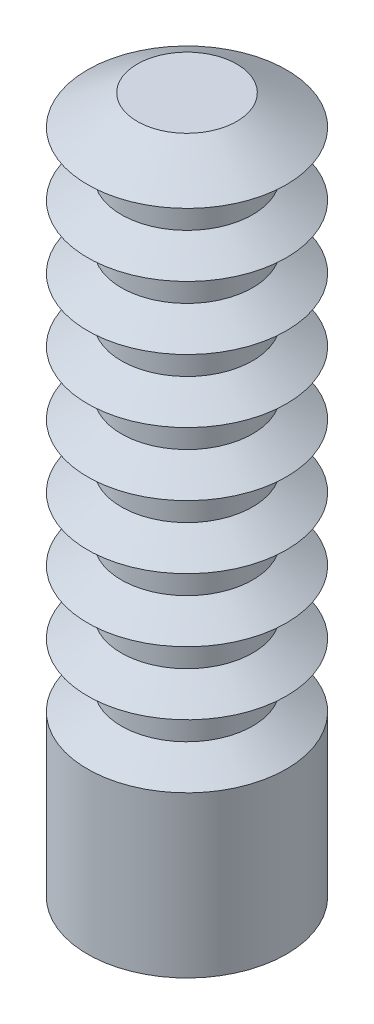
SolidWorks part; units mm, degrees
ref_plane "Front Plane" through (0, 0, 0) normal (0, 0, 1) x (1, 0, 0)
ref_plane "Top Plane" through (0, 0, 0) normal (0, 1, 0) x (1, 0, 0)
ref_plane "Right Plane" through (0, 0, 0) normal (1, 0, 0) x (0, 0, -1)
sketch "Sketch1" plane through (0, 0, 0) normal (0, 0, 1) x (1, 0, 0)
  line L0 (-2.9316, 34.2) -> (-2.9316, 31.2) construction
  line L1 (-0.4316, 32.7) -> (-2.1316, 31.68)
  line L2 (-5.4316, 34.2) -> (-5.4316, 0) construction
  line L3 (-2.1316, 31.68) -> (-2.1316, 30.54)
  line L4 (-2.9316, 34.2) -> (-0.4316, 32.7)
  line L5 (-3.1389, 32.0142) -> (-1.9958, 32.7)
  line L6 (-2.9316, 34.2) -> (-5.4316, 34.2)
  line L7 (-5.4316, 33.4) -> (-3.1389, 33.4)
  line L8 (-0.4316, 0) -> (-0.4316, -0.8)
  line L9 (-2.6564, 33.1045) -> (-3.1389, 33.4)
  line L10 (-3.1389, 33.4) -> (-1.9958, 32.7)
  line L11 (-0.4316, -0.8) -> (-5.4316, -0.8)
  line L12 (-3.1389, 28.8342) -> (-1.9958, 29.52)
  line L13 (-3.1389, 25.6542) -> (-1.9958, 26.34)
  line L14 (-3.1389, 30.22) -> (-3.1389, 32.0142)
  line L15 (-3.1389, 22.4742) -> (-1.9958, 23.16)
  line L16 (-2.1316, 30.54) -> (-0.4316, 29.52)
  line L17 (-3.1389, 19.2942) -> (-1.9958, 19.98)
  line L18 (-3.1389, 30.22) -> (-1.9958, 29.52)
  line L19 (-0.4316, 29.52) -> (-2.1316, 28.5)
  line L20 (-3.1389, 16.1142) -> (-1.9958, 16.8)
  line L21 (-2.1316, 28.5) -> (-2.1316, 27.36)
  line L22 (-3.1389, 27.04) -> (-3.1389, 28.8342)
  line L23 (-2.1316, 27.36) -> (-0.4316, 26.34)
  line L24 (-3.1389, 27.04) -> (-1.9958, 26.34)
  line L25 (-0.4316, 26.34) -> (-2.1316, 25.32)
  line L26 (-3.1389, 12.9342) -> (-1.9958, 13.62)
  line L27 (-2.1316, 25.32) -> (-2.1316, 24.18)
  line L28 (-3.1389, 23.86) -> (-3.1389, 25.6542)
  line L29 (-2.9316, 34.2) -> (-2.9316, 30.7) construction
  line L30 (-5.4316, 34.2) -> (-5.4316, 33.4)
  line L31 (-2.1316, 24.18) -> (-0.4316, 23.16)
  line L32 (-3.1389, 9.7542) -> (-1.9958, 10.44)
  line L33 (-3.1389, 23.86) -> (-1.9958, 23.16)
  line L34 (-5.4316, -0.8) -> (-5.4316, 0)
  line L35 (-0.4316, 23.16) -> (-2.1316, 22.14)
  line L36 (-5.4316, 0) -> (-1.2316, 0)
  line L37 (-2.1316, 22.14) -> (-2.1316, 21)
  line L38 (-3.1389, 20.68) -> (-3.1389, 22.4742)
  line L39 (-2.1316, 21) -> (-0.4316, 19.98)
  line L40 (-3.1389, 20.68) -> (-1.9958, 19.98)
  line L41 (-0.4316, 19.98) -> (-2.1316, 18.96)
  line L43 (-2.1316, 18.96) -> (-2.1316, 17.82)
  line L44 (-3.1389, 17.5) -> (-3.1389, 19.2942)
  line L45 (-2.1316, 17.82) -> (-0.4316, 16.8)
  line L46 (-3.1389, 17.5) -> (-1.9958, 16.8)
  line L47 (-0.4316, 16.8) -> (-2.1316, 15.78)
  line L49 (-2.1316, 15.78) -> (-2.1316, 14.64)
  line L50 (-3.1389, 14.32) -> (-3.1389, 16.1142)
  line L51 (-2.1316, 14.64) -> (-0.4316, 13.62)
  line L52 (-3.1389, 14.32) -> (-1.9958, 13.62)
  line L53 (-0.4316, 13.62) -> (-2.1316, 12.6)
  line L55 (-2.1316, 12.6) -> (-2.1316, 11.46)
  line L56 (-3.1389, 11.14) -> (-3.1389, 12.9342)
  line L57 (-2.1316, 11.46) -> (-0.4316, 10.44)
  line L58 (-3.1389, 11.14) -> (-1.9958, 10.44)
  line L59 (-0.4316, 10.44) -> (-2.1316, 9.42)
  line L60 (-1.9958, 10.44) -> (-3.1543, 9.7449)
  line L61 (-2.1316, 9.42) -> (-2.1316, 8.28)
  line L62 (-3.1389, 7.96) -> (-3.1389, 9.7542)
  line L63 (-2.9316, 31.02) -> (-0.4316, 29.52) [skipped]
  line L64 (-2.1316, 8.28) -> (-0.4316, 7.26)
  line L65 (-2.9316, 27.84) -> (-0.4316, 26.34) [skipped]
  line L66 (-2.9316, 24.66) -> (-0.4316, 23.16) [skipped]
  line L67 (-2.9316, 21.48) -> (-0.4316, 19.98) [skipped]
  line L68 (-2.9316, 18.3) -> (-0.4316, 16.8) [skipped]
  line L69 (-2.9316, 15.12) -> (-0.4316, 13.62) [skipped]
  line L70 (-2.9316, 11.94) -> (-0.4316, 10.44) [skipped]
  line L71 (-3.1389, 7.96) -> (-1.9958, 7.26)
  line L73 (-0.4316, 7.26) -> (-0.4316, 0)
  line L75 (-1.2316, 0) -> (-1.2316, 6.796)
  line L76 (-1.9958, 7.26) -> (-1.2316, 6.796)
  point P9 (-2.9316, 32.7)
  dimension "D4" = 3.5
  dimension "D2" = 3
  dimension "D3" = 2.5
  dimension "D6" = 0.8
  dimension "D10" = 0.8
  dimension "D9" = 8
revolve "Revolve1" add sketch "Sketch1" angle 360 about L2
